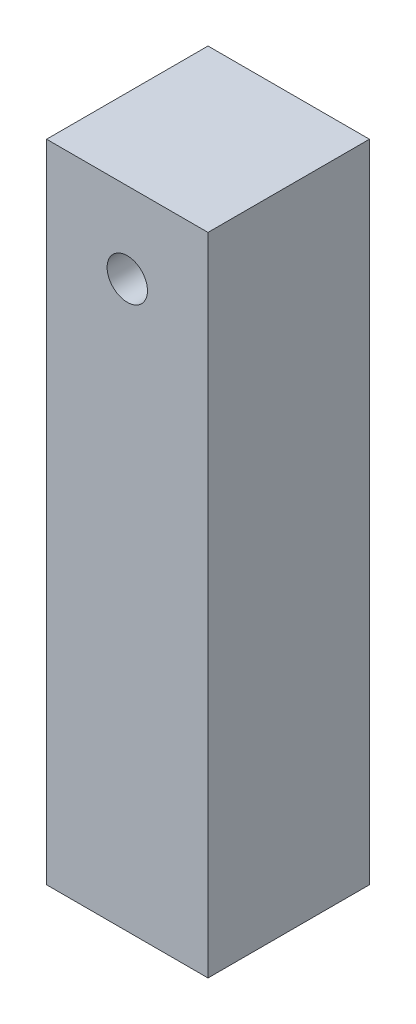
SolidWorks part; units mm, degrees
ref_plane "Front Plane" through (0, 0, 0) normal (0, 0, 1) x (1, 0, 0)
ref_plane "Top Plane" through (0, 0, 0) normal (0, 1, 0) x (1, 0, 0)
ref_plane "Right Plane" through (0, 0, 0) normal (1, 0, 0) x (0, 0, -1)
sketch "Sketch1" plane through (0, 0, 0) normal (0, 1, 0) x (1, 0, 0)
  line L1 (10.867, 11.9144) -> (-14.533, 11.9144)
  line L2 (10.867, 11.9144) -> (10.867, -13.4856)
  line L3 (10.867, -13.4856) -> (-14.533, -13.4856)
  line L4 (-14.533, 11.9144) -> (-14.533, -13.4856)
  line L5 (10.867, 11.9144) -> (-14.533, -13.4856) construction
  line L6 (10.867, -13.4856) -> (-14.533, 11.9144) construction
  point P0 (-1.833, -0.7856)
  dimension "D1" = 25.4
  dimension "D2" = 25.4
extrude "Boss-Extrude1" add sketch "Sketch1" along normal blind 101.6
sketch "Sketch2" plane through (0, 0, 13.4856) normal (0, 0, 1) x (1, 0, 0)
  line L0 (-14.533, 101.6) -> (10.867, 101.6) construction
  line L1 (10.867, 101.6) -> (10.867, 0) construction
  circle A0 centre (-1.833, 88.9) radius 3.175
  dimension "D1" = 6.35
  dimension "D2" = 12.7
  dimension "D3" = 12.7
extrude "Cut-Extrude1" cut sketch "Sketch2" against normal blind 101.6
